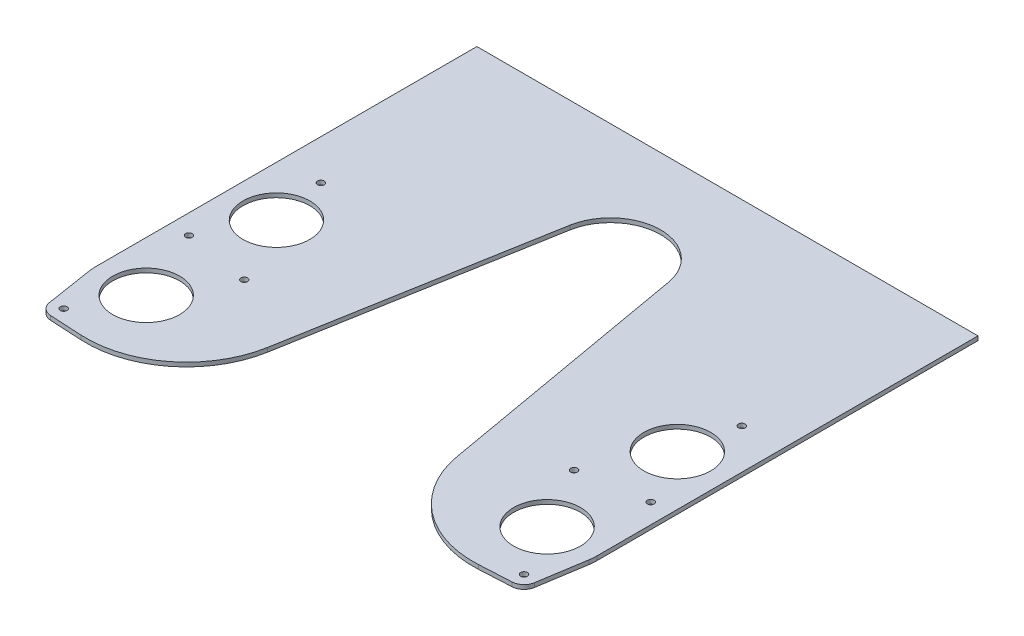
SolidWorks part; units mm, degrees
material "PC High Viscosity"
ref_plane "Front" through (0, 0, 0) normal (0, 0, 1) x (1, 0, 0)
ref_plane "Top" through (0, 0, 0) normal (0, 1, 0) x (1, 0, 0)
ref_plane "Right" through (0, 0, 0) normal (1, 0, 0) x (0, 0, -1)
sketch "Sketch1" plane through (0, 0, 0) normal (0, 1, 0) x (1, 0, 0)
  line L0 (-190.5, 0) -> (-190.5, -69.0534) construction
  line L3 (0, 0) -> (-381, 0)
  line L4 (-381, -289.5092) -> (-381, 0)
  line L5 (-228.0212, -82.284) -> (-262.4599, -277.5958)
  line L9 (-366.0031, -339.1349) -> (-341.6138, -340.4528)
  line L11 (-380.5328, -295.4575) -> (-374.8974, -331.1109)
  line L12 (-0.4672, -295.4575) -> (-6.1026, -331.1109)
  line L14 (-14.9969, -339.1349) -> (-39.3862, -340.4528)
  line L15 (-152.9788, -82.284) -> (-118.5401, -277.5958)
  line L16 (0, -289.5092) -> (0, 0)
  arc A0 (-152.9788, -82.284) -> (-228.0212, -82.284) centre (-190.5, -88.9) ccw
  circle A1 centre (-342.9, -190.5) radius 25.4
  circle A3 centre (-350.5065, -149.0655) radius 2.5527
  arc A8 (-374.8974, -331.1109) -> (-366.0031, -339.1349) centre (-365.4892, -329.6238) ccw
  circle A10 centre (-342.9, -289.5092) radius 25.4
  circle A11 centre (-342.9, -289.5092) radius 14.3129 construction
  arc A13 (-381, -289.5092) -> (-380.5328, -295.4575) centre (-342.9, -289.5092) ccw
  circle A14 centre (-365.4892, -329.6238) radius 2.5527
  circle A16 centre (-342.9, -289.5092) radius 38.1 construction
  circle A17 centre (-342.9, -190.5) radius 38.1 construction
  arc A21 (-341.6138, -340.4528) -> (-262.4599, -277.5958) centre (-337.5023, -264.3638) ccw
  circle A22 centre (-366.0356, -233.8423) radius 2.5527
  circle A23 centre (-315.891, -241.9759) radius 2.5527
  circle A24 centre (-65.109, -241.9759) radius 2.5527
  circle A25 centre (-14.9644, -233.8423) radius 2.5527
  arc A26 (-39.3862, -340.4528) -> (-118.5401, -277.5958) centre (-43.4977, -264.3638) cw
  circle A27 centre (-15.5108, -329.6238) radius 2.5527
  arc A28 (0, -289.5092) -> (-0.4672, -295.4575) centre (-38.1, -289.5092) cw
  circle A29 centre (-38.1, -289.5092) radius 25.4
  arc A30 (-6.1026, -331.1109) -> (-14.9969, -339.1349) centre (-15.5108, -329.6238) cw
  circle A31 centre (-30.4935, -149.0655) radius 2.5527
  circle A32 centre (-38.1, -190.5) radius 25.4
  circle A33 centre (-366.0356, -233.8423) radius 2.5527 construction
  circle A34 centre (-315.891, -241.9759) radius 2.5527 construction
  dimension "D3" = 190.5
  dimension "D4" = 38.1
  dimension "D5" = 50.8
  dimension "D6" = 5.1054
  dimension "D7" = 25.4
  dimension "D8" = 9.525
  dimension "D9" = 50.8
  dimension "D10" = 76.2
  dimension "D11" = 20
  dimension "D12" = 38.1
  dimension "D13" = 76.2
  dimension "D1" = 381
extrude "Boss-Extrude1" add sketch "Sketch1" along normal blind 3.175
